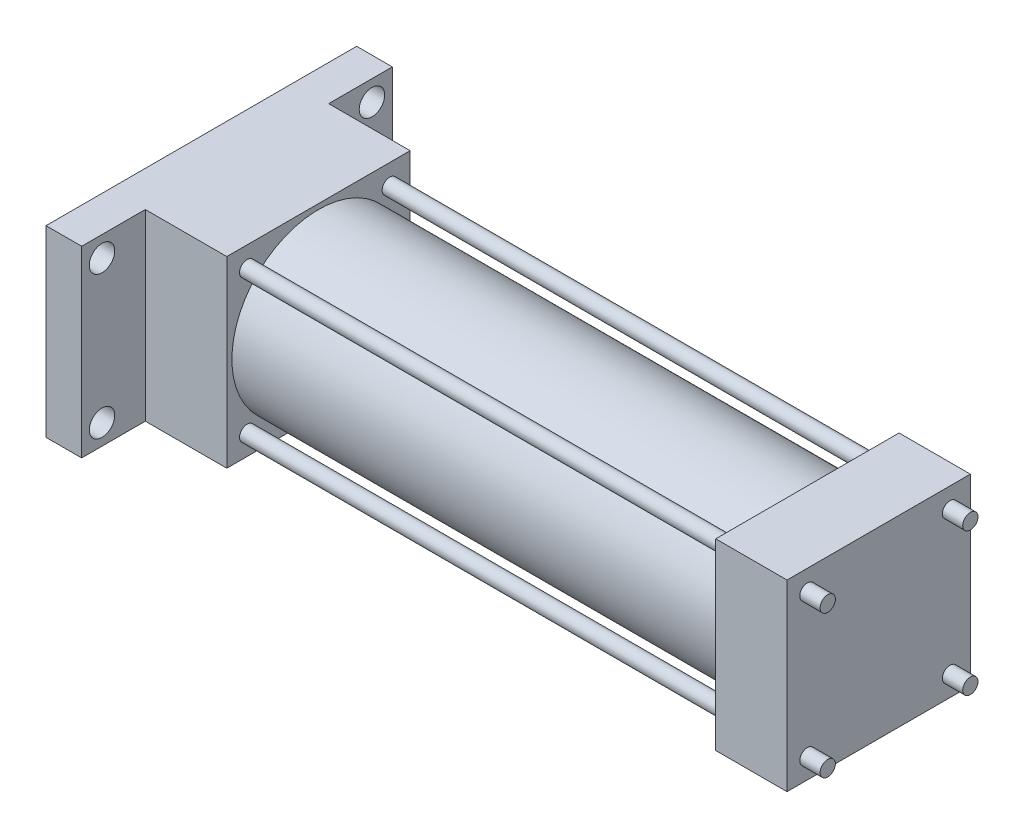
SolidWorks part; units mm, degrees
material "PW50:30:C1:0:1:2:Re:16:"
ref_plane "front" through (0, 0, 0) normal (0, 0, 1) x (1, 0, 0)
ref_plane "top" through (0, 0, 0) normal (0, 1, 0) x (1, 0, 0)
ref_plane "side" through (0, 0, 0) normal (1, 0, 0) x (0, 0, -1)
sketch "Sketch1" plane through (0, 0, 0) normal (1, 0, 0) x (0, 0, -1)
  line L0 (-57.15, 57.15) -> (57.15, 57.15)
  line L1 (-57.15, 57.15) -> (-57.15, -57.15)
  line L2 (57.15, -57.15) -> (-57.15, -57.15)
  line L3 (57.15, -57.15) -> (57.15, 57.15)
  line L4 (0, 57.15) -> (0, 0) construction
  line L5 (57.15, 0) -> (0, 0) construction
  dimension "D1" = 114.3
extrude "Base-Extrude" add sketch "Sketch1" against normal blind 44.45
sketch "Sketch2" plane through (-44.45, 0, 0) normal (-1, 0, 0) x (0, 0, 1)
  circle A0 centre (0, 0) radius 53.975
  dimension "D1" = 107.95
extrude "Boss-Extrude1" add sketch "Sketch2" along normal blind 304.8
sketch "Sketch3" plane through (-349.25, 0, 0) normal (-1, 0, 0) x (0, 0, 1)
  line L4 (57.15, -57.15) -> (57.15, 57.15)
  line L5 (57.15, 57.15) -> (-57.15, 57.15)
  line L6 (-57.15, 57.15) -> (-57.15, -57.15)
  line L7 (-57.15, -57.15) -> (57.15, -57.15)
  line L8 (57.15, -57.15) -> (57.15, 57.15)
  line L9 (57.15, 57.15) -> (-57.15, 57.15)
  line L10 (-57.15, 57.15) -> (-57.15, -57.15)
  line L11 (-57.15, -57.15) -> (57.15, -57.15)
  dimension "D1" = 0
extrude "Boss-Extrude2" add sketch "Sketch3" along normal blind 73.025
sketch "Sketch4" plane through (-422.275, 0, 0) normal (-1, 0, 0) x (0, 0, 1)
  circle A0 centre (0, 0) radius 25.4
  dimension "D1" = 50.8
extrude "Boss-Extrude3" add sketch "Sketch4" along normal blind 25.4
sketch "Sketch5" plane through (-447.675, 0, 0) normal (-1, 0, 0) x (0, 0, 1)
  circle A0 centre (0, 0) radius 17.4625
  dimension "D1" = 34.925
extrude "Cut-Extrude1" cut sketch "Sketch5" against normal up to surface (403.225 mm away)
sketch "Sketch6" plane through (-349.25, 0, 0) normal (1, 0, 0) x (0, 0, -1)
  line L0 (-57.15, 57.15) -> (57.15, 57.15) construction
  line L1 (-57.15, -57.15) -> (-57.15, 57.15) construction
  line L2 (0, 57.15) -> (0, 0) construction
  line L3 (-57.15, 0) -> (0, 0) construction
  circle A0 centre (-44.45, 44.45) radius 4.7625
  circle A1 centre (44.45, 44.45) radius 4.7625
  circle A2 centre (44.45, -44.45) radius 4.7625
  circle A3 centre (-44.45, -44.45) radius 4.7625
  dimension "D2" = 9.525
  dimension "D1" = 12.7
  dimension "D3" = 12.7
extrude "Boss-Extrude4" add sketch "Sketch6" along normal offset from surface (361.95 mm away) 12.7
sketch "Sketch7" plane through (-422.275, 0, 0) normal (-1, 0, 0) x (0, 0, 1)
  line L0 (-96.8375, -57.15) -> (96.8375, -57.15)
  line L1 (-96.8375, -57.15) -> (-96.8375, 57.15)
  line L2 (96.8375, 57.15) -> (-96.8375, 57.15)
  line L3 (96.8375, 57.15) -> (96.8375, -57.15)
  line L4 (57.15, 57.15) -> (-57.15, 57.15) construction
  line L5 (-57.15, -57.15) -> (57.15, -57.15) construction
  line L7 (0, 57.15) -> (0, 0) construction
  line L12 (-84.1375, 0) -> (0, 0) construction
  dimension "D1" = 193.675
extrude "Boss-Extrude5" add sketch "Sketch7" against normal blind 22.225
sketch "Sketch8" plane through (-422.275, 0, 0) normal (-1, 0, 0) x (0, 0, 1)
  line L0 (-96.8375, -57.15) -> (96.8375, -57.15) construction
  line L1 (96.8375, 57.15) -> (96.8375, -57.15) construction
  circle A0 centre (84.1375, -44.45) radius 7.9375
  dimension "D1" = 15.875
  dimension "D2" = 12.7
  dimension "D3" = 12.7
extrude "Cut-Extrude2" cut sketch "Sketch8" against normal up to next
pattern_linear "LPattern2" count 2 spacing 168.275 along (0, 0, -1) count 2 spacing 88.9 along (0, 1, 0) of "Cut-Extrude2"
